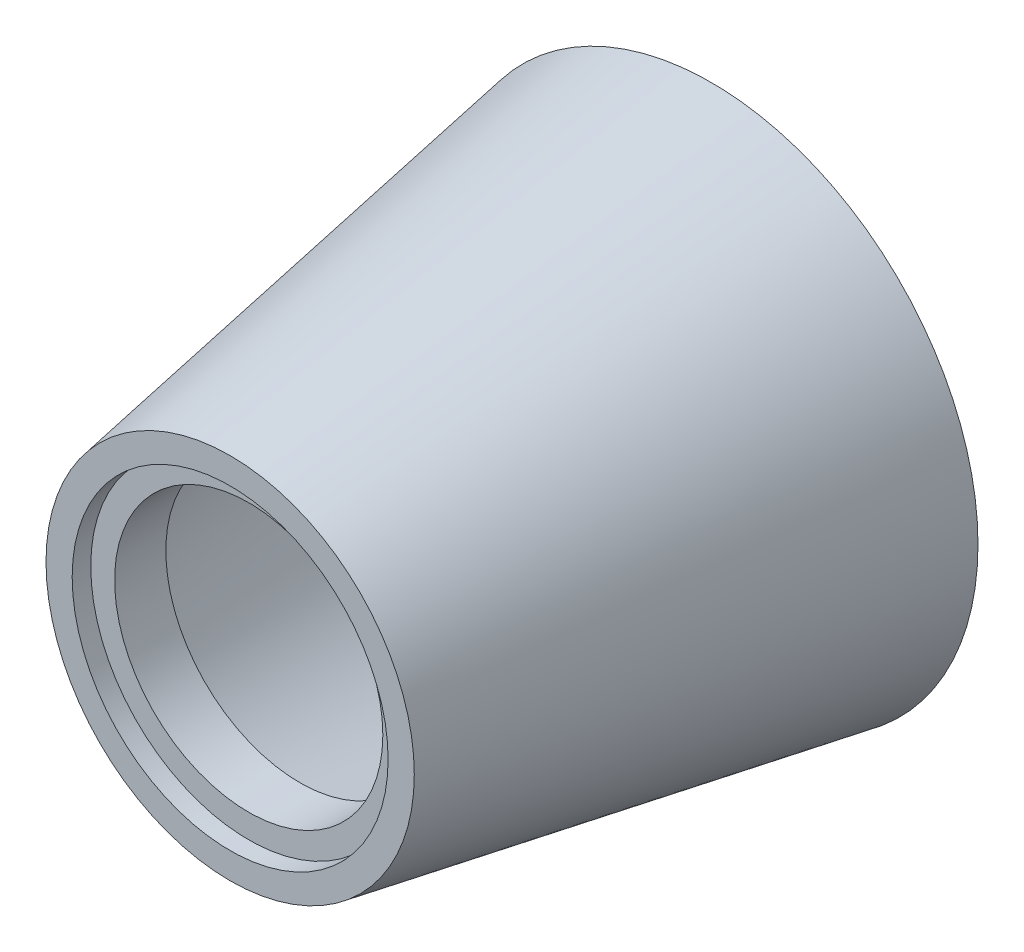
SolidWorks part; units mm, degrees
ref_plane "Front Plane" through (0, 0, 0) normal (0, 0, 1) x (1, 0, 0)
ref_plane "Top Plane" through (0, 0, 0) normal (0, 1, 0) x (1, 0, 0)
ref_plane "Right Plane" through (0, 0, 0) normal (1, 0, 0) x (0, 0, -1)
sketch "Sketch1" plane through (0, 0, 0) normal (1, 0, 0) x (0, 0, -1)
  line L0 (-74.7958, 72.1588) -> (-74.7958, 85)
  line L1 (-74.7958, -85) -> (-74.7958, 85) construction
  line L2 (-74.7958, 85) -> (-84.7958, 85)
  line L3 (-84.7958, 85) -> (-84.7958, -85) construction
  line L4 (-84.7958, 85) -> (-84.7958, 99.0836)
  line L5 (-84.7958, 99.0836) -> (174.1141, 143.49)
  line L6 (174.1141, 143.49) -> (174.1141, 128.8201) construction
  line L7 (174.1141, 143.49) -> (174.1141, 121.2868)
  line L8 (174.1141, 128.8201) -> (174.1141, 57.6264) construction
  line L9 (174.1141, 121.2868) -> (-47.2428, 83.3212)
  line L10 (-47.2428, 83.3212) -> (-47.2428, 72.1588)
  line L11 (-47.2428, 72.1588) -> (-74.7958, 72.1588)
  line L12 (-108.4064, 0) -> (314.7851, 0) construction
revolve "Revolve1" add sketch "Sketch1" angle 360 about L12
